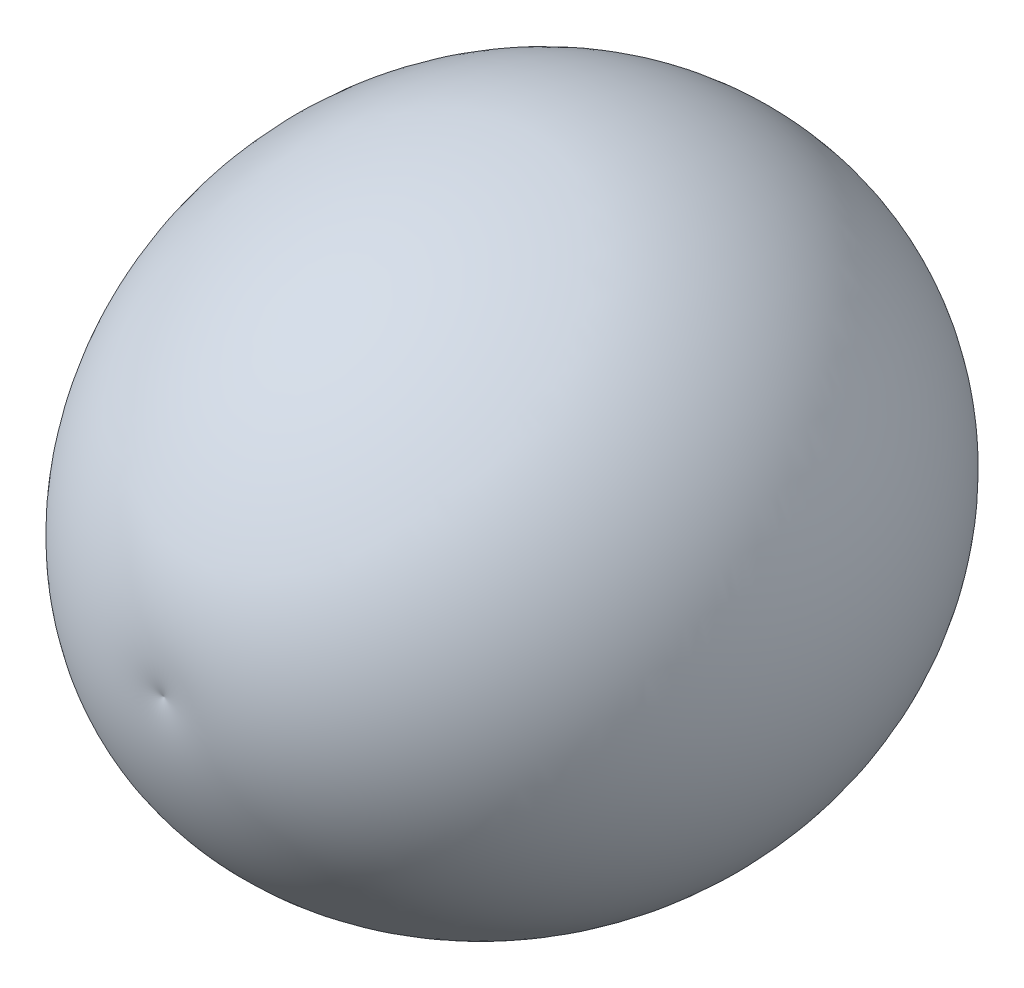
SolidWorks part; units mm, degrees
ref_plane "Front Plane" through (0, 0, 0) normal (0, 0, 1) x (1, 0, 0)
ref_plane "Top Plane" through (0, 0, 0) normal (0, 1, 0) x (1, 0, 0)
ref_plane "Right Plane" through (0, 0, 0) normal (1, 0, 0) x (0, 0, -1)
sketch "Sketch1" plane through (0, 0, 0) normal (0, 1, 0) x (1, 0, 0)
  line L0 (0, 315.6302) -> (0, 0) construction
  line L1 (0, 0) -> (0, 315.6302)
  spline S0 degree 4 poles (0, 0) (0.0618, -0.0261) (0.1862, -0.0763) (0.4381, -0.1685) (0.8205, -0.294) (1.2707, -0.4273) (1.919, -0.5992) (2.7031, -0.7808) (3.6244, -0.9625) (4.6836, -1.1352) (6.0132, -1.3124) (7.7503, -1.4823) (9.8966, -1.6012) (12.4499, -1.624) (15.1369, -1.5297) (18.0288, -1.3127) (21.1197, -0.9543) (25.2751, -0.2997) (30.4607, 0.8109) (36.4202, 2.4784) (44.7537, 5.4254) (54.2103, 9.6739) (64.5739, 15.5079) (75.7699, 23.3303) (86.2103, 32.1343) (98.504, 44.5072) (111.6583, 61.2075) (124.2177, 82.6381) (134.5117, 109.0887) (140.5392, 136.824) (142.1247, 165.1656) (139.5089, 189.8709) (134.3642, 210.4984) (128.7718, 225.4035) (124.3288, 235.0361) (120.1562, 242.825) (116.5397, 248.8988) (111.676, 256.276) (106.3632, 263.3421) (100.6155, 270.0598) (94.452, 276.392) (89.2803, 281.2117) (83.8774, 285.7707) (78.2539, 290.0548) (72.6221, 293.9126) (67.0166, 297.3646) (61.4691, 300.4332) (56.0076, 303.1428) (51.0157, 305.345) (46.5379, 307.1151) (42.6078, 308.5214) (39.2504, 309.6233) (35.8646, 310.6354) (32.4535, 311.5568) (29.0182, 312.3866) (25.563, 313.1239) (22.0873, 313.768) (18.5988, 314.3184) (15.5292, 314.7173) (12.8997, 315) (10.6912, 315.1959) (8.9466, 315.3288) (7.1997, 315.4349) (5.5866, 315.5163) (3.874, 315.5749) (2.4607, 315.6128) (0.4986, 315.633) (-0.6344, 315.6315) (-2.2927, 315.6143) (-3.6161, 315.5814) (-5.1674, 315.5337) (-6.8208, 315.4567) (-8.8073, 315.3395) (-10.7381, 315.193) (-12.6976, 315.0174) (-14.6361, 314.8126) (-16.5815, 314.5787) (-19.0023, 314.2501) (-21.9024, 313.7979) (-25.2698, 313.1864) (-29.1131, 312.3699) (-32.9455, 311.435) (-36.7644, 310.3815) (-40.5653, 309.209) (-43.3887, 308.2447) (-45.2574, 307.5646) (-46.1884, 307.2153) knots 0 0 0 0 0 0.000517 0.001033 0.002067 0.0031 0.004133 0.0062 0.008266 0.010333 0.012399 0.016532 0.021709 0.026886 0.032063 0.03724 0.044045 0.05085 0.06446 0.07807 0.09168 0.118899 0.144216 0.169532 0.196752 0.223971 0.278411 0.33285 0.387289 0.441728 0.496167 0.550606 0.577826 0.605045 0.618655 0.632265 0.645875 0.659484 0.686704 0.700314 0.713924 0.727533 0.741143 0.754753 0.768363 0.780101 0.791839 0.803577 0.815315 0.822119 0.828924 0.835729 0.842534 0.849339 0.856144 0.862949 0.869754 0.876559 0.883363 0.886766 0.890168 0.893571 0.896973 0.900003 0.903032 0.906061 0.909091 0.912858 0.914741 0.916625 0.920391 0.924158 0.927925 0.931692 0.935459 0.939226 0.942992 0.946759 0.954293 0.961827 0.96936 0.97702 0.98468 0.99234 1 1 1 1 1 construction
  spline S1 degree 4 poles (0, 0) (0.0618, -0.0261) (0.1862, -0.0763) (0.4381, -0.1685) (0.8205, -0.294) (1.2707, -0.4273) (1.919, -0.5992) (2.7031, -0.7808) (3.6244, -0.9625) (4.6836, -1.1352) (6.0132, -1.3124) (7.7503, -1.4823) (9.8966, -1.6012) (12.4499, -1.624) (15.1369, -1.5297) (18.0288, -1.3127) (21.1197, -0.9543) (25.2751, -0.2997) (30.4607, 0.8109) (36.4202, 2.4784) (44.7537, 5.4254) (54.2103, 9.6739) (64.5739, 15.5079) (75.7699, 23.3303) (86.2103, 32.1343) (98.504, 44.5072) (111.6583, 61.2075) (124.2177, 82.6381) (134.5117, 109.0887) (140.5392, 136.824) (142.1247, 165.1656) (139.5089, 189.8709) (134.3642, 210.4984) (128.7718, 225.4035) (124.3288, 235.0361) (120.1562, 242.825) (116.5397, 248.8988) (111.676, 256.276) (106.3632, 263.3421) (100.6155, 270.0598) (94.452, 276.392) (89.2803, 281.2117) (83.8774, 285.7707) (78.2539, 290.0548) (72.6221, 293.9126) (67.0166, 297.3646) (61.4691, 300.4332) (56.0076, 303.1428) (51.0157, 305.345) (46.5379, 307.1151) (42.6078, 308.5214) (39.2504, 309.6233) (35.8646, 310.6354) (32.4535, 311.5568) (29.0182, 312.3866) (25.563, 313.1239) (22.0873, 313.768) (18.5988, 314.3184) (15.5292, 314.7173) (12.8997, 315) (10.6912, 315.1959) (8.9466, 315.3288) (7.1997, 315.4349) (5.5866, 315.5163) (3.874, 315.5749) (2.4607, 315.6128) (1.0735, 315.6271) (0.3575, 315.6302) (0, 315.6302) knots 0 0 0 0 0 0.000517 0.001033 0.002067 0.0031 0.004133 0.0062 0.008266 0.010333 0.012399 0.016532 0.021709 0.026886 0.032063 0.03724 0.044045 0.05085 0.06446 0.07807 0.09168 0.118899 0.144216 0.169532 0.196752 0.223971 0.278411 0.33285 0.387289 0.441728 0.496167 0.550606 0.577826 0.605045 0.618655 0.632265 0.645875 0.659484 0.686704 0.700314 0.713924 0.727533 0.741143 0.754753 0.768363 0.780101 0.791839 0.803577 0.815315 0.822119 0.828924 0.835729 0.842534 0.849339 0.856144 0.862949 0.869754 0.876559 0.883363 0.886766 0.890168 0.893571 0.896973 0.900003 0.903032 0.906061 0.909091 0.909091 0.909091 0.909091 0.909091
revolve "Revolve1" add sketch "Sketch1" angle 360 about L0
